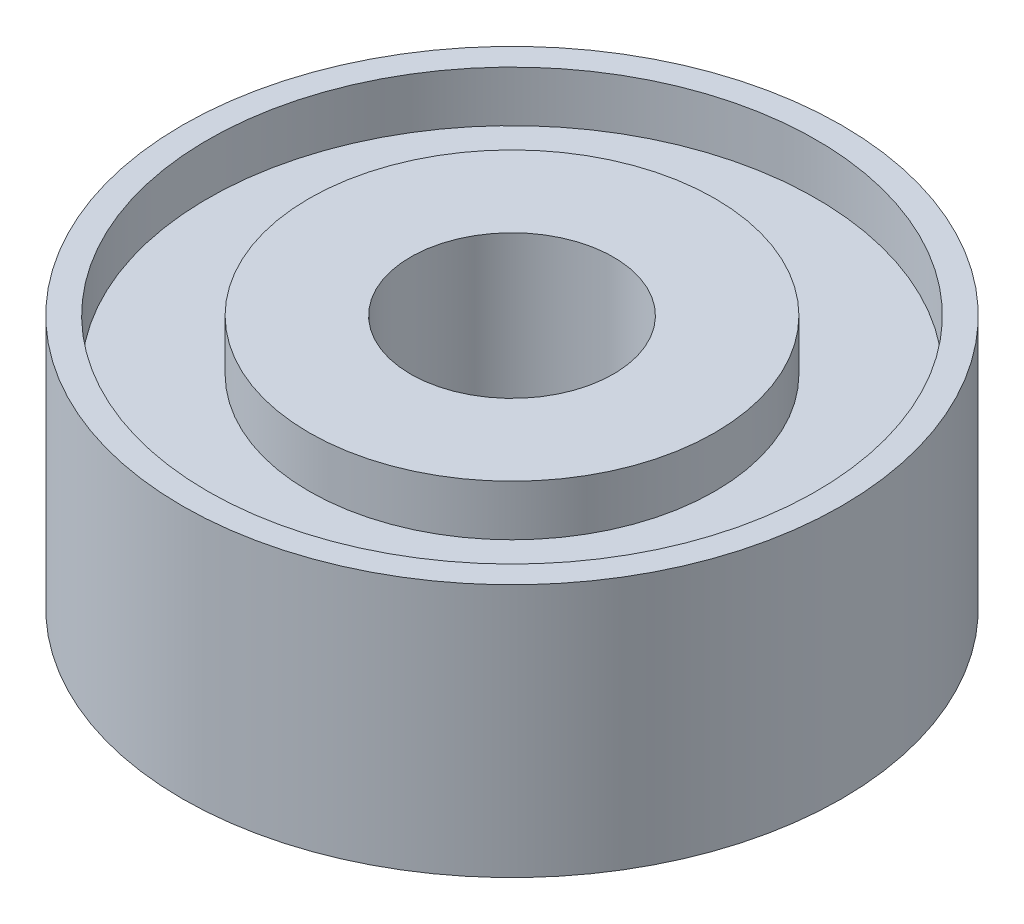
SolidWorks part; units mm, degrees
ref_plane "Front Plane" through (0, 0, 0) normal (0, 0, 1) x (1, 0, 0)
ref_plane "Top Plane" through (0, 0, 0) normal (0, 1, 0) x (1, 0, 0)
ref_plane "Right Plane" through (0, 0, 0) normal (1, 0, 0) x (0, 0, -1)
sketch "Sketch2" plane through (0, 0, 0) normal (0, 1, 0) x (1, 0, 0)
  circle A0 centre (0, 0) radius 6.5
  circle A1 centre (0, 0) radius 2
extrude "Boss-Extrude1" add sketch "Sketch2" along normal blind 5
sketch "Sketch3" plane through (0, 5, 0) normal (0, 1, 0) x (1, 0, 0)
  circle A0 centre (0, 0) radius 6
  circle A1 centre (0, 0) radius 4
extrude "Cut-Extrude1" cut sketch "Sketch3" against normal blind 1
sketch "Sketch4" plane through (0, 0, 0) normal (0, -1, 0) x (1, 0, 0)
  circle A0 centre (0, 0) radius 6
  circle A1 centre (0, 0) radius 4
extrude "Cut-Extrude2" cut sketch "Sketch4" against normal blind 1 contours A0
